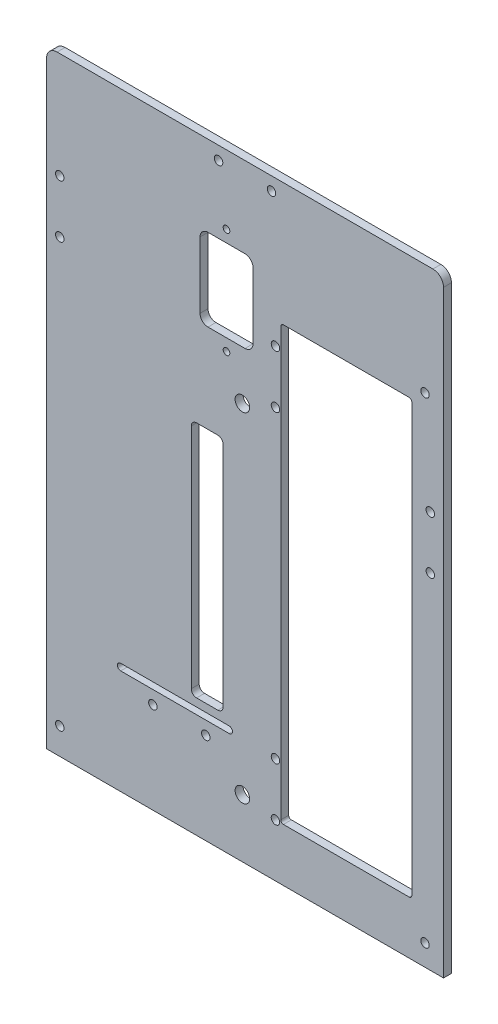
SolidWorks part; units mm, degrees
ref_plane "前视基准面" through (0, 0, 0) normal (0, 0, 1) x (1, 0, 0)
ref_plane "上视基准面" through (0, 0, 0) normal (0, 1, 0) x (1, 0, 0)
ref_plane "右视基准面" through (0, 0, 0) normal (1, 0, 0) x (0, 0, -1)
sketch "草图1" plane through (0, 0, 0) normal (0, 0, 1) x (1, 0, 0)
  line L1 (0, 0) -> (150, 0)
  line L2 (0, 0) -> (0, 230)
  line L3 (0, 230) -> (150, 230)
  line L4 (150, 0) -> (150, 230)
  dimension "D1" = 230
  dimension "D2" = 150
extrude "凸台-拉伸1" add sketch "草图1" along normal blind 3
sketch "草图2" plane through (0, 0, 3) normal (0, 0, 1) x (1, 0, 0)
  line L0 (86.5, 20) -> (86.5, 40) construction
  line L1 (86.5, 155) -> (86.5, 175) construction
  line L2 (150, 0) -> (150, 230) construction
  line L3 (0, 0) -> (150, 0) construction
  line L4 (0, 230) -> (0, 0) construction
  line L5 (5, 170) -> (5, 190) construction
  line L6 (65, 225) -> (85, 225) construction
  line L7 (150, 230) -> (0, 230) construction
  line L8 (75, 230) -> (75, 225) construction
  line L9 (145, 150) -> (145, 130) construction
  circle A0 centre (86.5, 20) radius 1.6
  circle A1 centre (86.5, 40) radius 1.6
  circle A2 centre (86.5, 155) radius 1.6
  circle A3 centre (86.5, 175) radius 1.6
  circle A4 centre (5, 10) radius 1.6
  circle A5 centre (143, 8) radius 1.6
  circle A6 centre (143, 188) radius 1.6
  circle A7 centre (5, 170) radius 1.6
  circle A8 centre (5, 190) radius 1.6
  circle A9 centre (65, 225) radius 1.6
  circle A10 centre (85, 225) radius 1.6
  circle A11 centre (145, 150) radius 1.6
  circle A12 centre (145, 130) radius 1.6
  dimension "D2" = 20
  dimension "D3" = 155
  dimension "D5" = 3.2
  dimension "D6" = 3.2
  dimension "D14" = 3.2
  dimension "D16" = 190
  dimension "D18" = 3.2
  dimension "D21" = 5
  dimension "D1" = 63.5
  dimension "D4" = 20
  dimension "D7" = 10
  dimension "D8" = 5
  dimension "D9" = 7
  dimension "D10" = 8
  dimension "D11" = 7
  dimension "D12" = 188
  dimension "D13" = 20
  dimension "D15" = 5
  dimension "D17" = 20
  dimension "D19" = 5
  dimension "D20" = 150
  dimension "D22" = 20
extrude "切除-拉伸1" cut sketch "草图2" against normal through all
sketch "草图3" plane through (0, 0, 3) normal (0, 0, 1) x (1, 0, 0)
  line L5 (28, 40.75) -> (69, 40.75) construction
  line L6 (28, 42) -> (69, 42)
  line L7 (28, 39.5) -> (69, 39.5)
  line L9 (0, 230) -> (0, 0) construction
  line L10 (48.5, 40.75) -> (48.5, 26.8817) construction
  arc A0 (28, 42) -> (28, 39.5) centre (28, 40.75) ccw
  arc A1 (69, 39.5) -> (69, 42) centre (69, 40.75) ccw
  circle A2 centre (40.19, 34.5) radius 1.6
  circle A3 centre (60.19, 34.5) radius 1.6
  point P2 (48.5, 40.75)
  dimension "D7" = 3.2
  dimension "D9" = 20
  dimension "D8" = 5
  dimension "D1" = 39.5
  dimension "D2" = 28
  dimension "D3" = 41
  dimension "D4" = 2.5
  dimension "D5" = 5
  dimension "D6" = 32.19
extrude "切除-拉伸2" cut sketch "草图3" against normal through all
sketch "草图4" plane through (0, 0, 3) normal (0, 0, 1) x (1, 0, 0)
  line L0 (69, 42) -> (28, 42) construction
  line L1 (56.69, 135) -> (64.69, 135)
  line L2 (54.69, 133) -> (54.69, 47)
  line L3 (56.69, 45) -> (64.69, 45)
  line L4 (66.69, 133) -> (66.69, 47)
  arc A1 (54.69, 47) -> (56.69, 45) centre (56.69, 47) ccw
  arc A2 (64.69, 45) -> (66.69, 47) centre (64.69, 47) ccw
  arc A3 (64.69, 135) -> (66.69, 133) centre (64.69, 133) cw
  arc A4 (56.69, 135) -> (54.69, 133) centre (56.69, 133) ccw
  circle A5 centre (60.19, 34.5) radius 1.6 construction
  point P8 (54.69, 45)
  point P11 (66.69, 45)
  point P16 (54.69, 135)
  dimension "D5" = 2
  dimension "D1" = 12
  dimension "D2" = 90
  dimension "D3" = 3
  dimension "D4" = 6.5
extrude "切除-拉伸3" cut sketch "草图4" against normal up to next
sketch "草图5" plane through (0, 0, 3) normal (0, 0, 1) x (1, 0, 0)
  line L0 (150, 0) -> (150, 230) construction
  line L1 (138, 20) -> (88.5, 20)
  line L2 (138, 20) -> (138, 183.5)
  line L3 (138, 183.5) -> (88.5, 183.5)
  line L4 (88.5, 20) -> (88.5, 183.5)
  line L5 (0, 0) -> (150, 0) construction
  dimension "D1" = 12
  dimension "D2" = 20
  dimension "D3" = 183.5
  dimension "D4" = 61.5
extrude "切除-拉伸4" cut sketch "草图5" against normal up to next
fillet "圆角1" radius 4 2 edges at (150, 230, 1.5) (0, 230, 1.5)
sketch "草图6" plane through (0, 0, 3) normal (0, 0, 1) x (1, 0, 0)
  line L0 (125, -9) -> (125, 9) construction
  line L1 (0, 0) -> (150, 0) construction
  line L2 (122, -9) -> (122, 9)
  line L3 (128, -9) -> (128, 9)
  arc A0 (122, -9) -> (128, -9) centre (125, -9) ccw
  arc A1 (128, 9) -> (122, 9) centre (125, 9) ccw
  point P4 (125, 0)
  dimension "D1" = 3
  dimension "D2" = 9
  dimension "D3" = 25
extrude "切除-拉伸5" [suppressed] cut sketch "草图6" against normal up to next
fillet "圆角2" [suppressed] radius 2
sketch "草图7" plane through (0, 0, 3) normal (0, 0, 1) x (1, 0, 0)
  line L0 (68, 164) -> (68, 204) construction
  line L1 (0, 226) -> (0, 0) construction
  line L2 (146, 230) -> (4, 230) construction
  line L3 (77.775, 170.1) -> (77.775, 197.9)
  line L4 (77.775, 197.9) -> (64.6207, 197.9)
  line L5 (64.6207, 197.9) -> (58.225, 191.9568)
  line L6 (58.225, 191.9568) -> (58.225, 176.0432)
  line L7 (58.225, 176.0432) -> (64.6207, 170.1)
  line L8 (64.6207, 170.1) -> (77.775, 170.1)
  line L9 (77.275, 170.6) -> (77.275, 197.4)
  line L10 (64.8172, 170.6) -> (77.275, 170.6)
  line L11 (58.725, 176.2611) -> (64.8172, 170.6)
  line L12 (58.725, 191.7389) -> (58.725, 176.2611)
  line L13 (64.8172, 197.4) -> (58.725, 191.7389)
  line L14 (77.275, 197.4) -> (64.8172, 197.4)
  line L15 (77.275, 170.6) -> (77.275, 197.4) construction
  line L16 (64.8172, 170.6) -> (77.275, 170.6) construction
  line L17 (58.725, 176.2611) -> (64.8172, 170.6) construction
  line L18 (58.725, 191.7389) -> (58.725, 176.2611) construction
  line L19 (64.8172, 197.4) -> (58.725, 191.7389) construction
  line L20 (77.275, 197.4) -> (64.8172, 197.4) construction
  circle A0 centre (68, 204) radius 1.25
  circle A1 centre (68, 164) radius 1.25
  point P3 (68, 184)
  dimension "D1" = 2.5
  dimension "D2" = 40
  dimension "D3" = 68
  dimension "D4" = 46
  dimension "D5" = 0
  dimension "D6" = 0.5
extrude "切除-拉伸6" cut sketch "草图7" against normal up to next
fillet "圆角3" radius 1 4 edges at (88.5, 20, 1.5) (138, 20, 1.5) (88.5, 183.5, 1.5) (138, 183.5, 1.5)
sketch "草图8" plane through (0, 0, 3) normal (0, 0, 1) x (1, 0, 0)
  line L0 (68, 184) -> (77.775, 184) construction
  line L1 (58, 168.5) -> (78, 168.5)
  line L2 (58, 168.5) -> (58, 199.5)
  line L3 (58, 199.5) -> (78, 199.5)
  line L4 (78, 168.5) -> (78, 199.5)
  line L5 (58, 168.5) -> (78, 199.5) construction
  line L6 (58, 199.5) -> (78, 168.5) construction
  line L7 (77.775, 170.1) -> (77.775, 197.9) construction
  line L8 (68, 204) -> (68, 199.5) construction
  point P0 (68, 184)
  dimension "D1" = 20
  dimension "D2" = 31
extrude "切除-拉伸7" cut sketch "草图8" against normal up to next
fillet "圆角4" radius 3 4 edges at (78, 168.5, 1.5) (58, 168.5, 1.5) (78, 199.5, 1.5) (58, 199.5, 1.5)
sketch "草图9" plane through (0, 0, 3) normal (0, 0, 1) x (1, 0, 0)
  line L0 (0, 113) -> (150, 113) construction
  line L1 (0, 226) -> (0, 0) construction
  line L2 (150, 0) -> (150, 226) construction
  line L3 (0, 0) -> (150, 0) construction
  line L4 (146, 230) -> (4, 230) construction
  circle A0 centre (74, 150) radius 2.75
  circle A1 centre (74, 22) radius 2.75
  circle A2 centre (74, 150) radius 5 construction
  circle A3 centre (74, 22) radius 5 construction
  point P9 (78, 113)
  dimension "D2" = 5.5
  dimension "D3" = 10
  dimension "D1" = 74
  dimension "D4" = 22
  dimension "D5" = 80
extrude "切除-拉伸8" cut sketch "草图9" against normal through all
